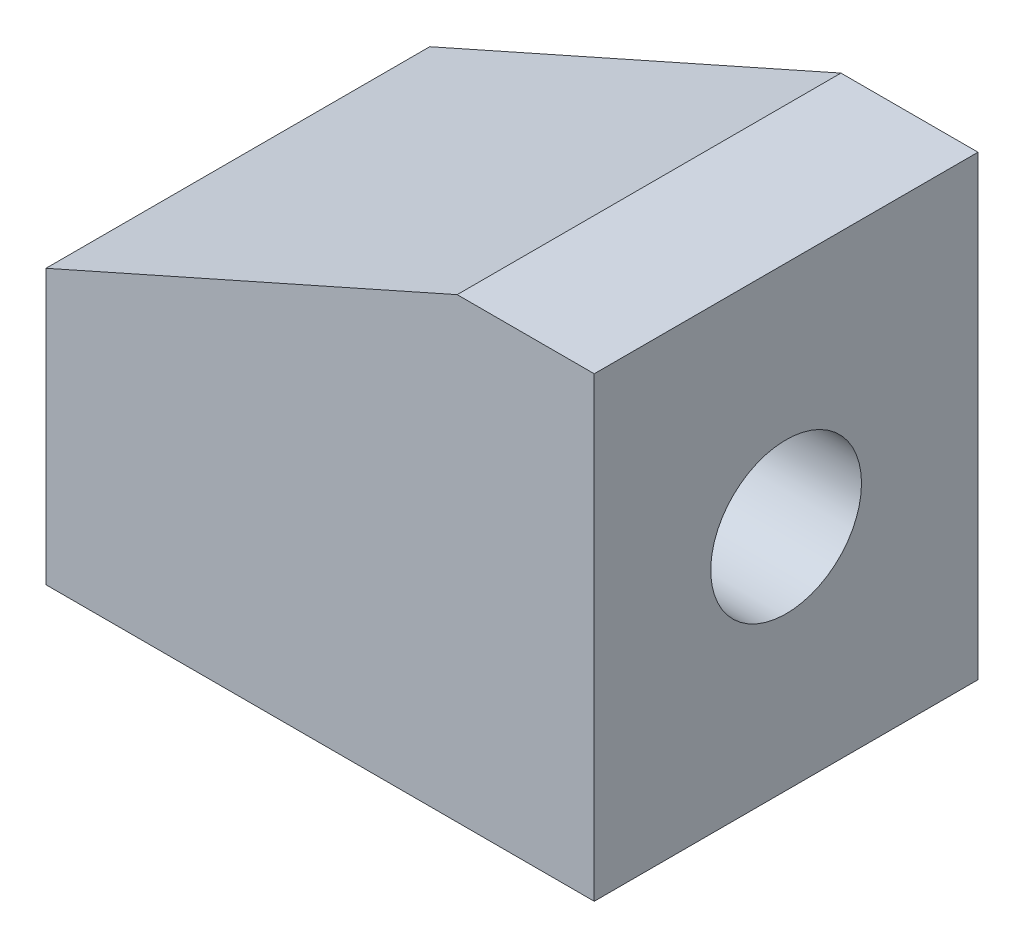
SolidWorks part; units mm, degrees
ref_plane "Front Plane" through (0, 0, 0) normal (0, 0, 1) x (1, 0, 0)
ref_plane "Top Plane" through (0, 0, 0) normal (0, 1, 0) x (1, 0, 0)
ref_plane "Right Plane" through (0, 0, 0) normal (1, 0, 0) x (0, 0, -1)
sketch "Sketch1" plane through (0, 0, 0) normal (0, 0, 1) x (1, 0, 0)
  line L0 (-30, 15) -> (15, 35)
  line L1 (-30, -15) -> (30, -15)
  line L2 (-30, -15) -> (-30, 15)
  line L5 (30, 35) -> (30, -15)
  line L6 (-30, 15) -> (30, -15) construction
  line L7 (15, 35) -> (30, 35)
  point P0 (0, 0)
  point P1 (0, 0)
  dimension "D1" = 60
  dimension "D2" = 30
  dimension "D3" = 15
  dimension "D4" = 50
  dimension "D5" = 35
extrude "Boss-Extrude1" add sketch "Sketch1" along normal blind 42
sketch "Sketch2" plane through (30, 0, 0) normal (1, 0, 0) x (0, 0, -1)
  line L0 (-42, -15) -> (0, -15) construction
  line L1 (-42, -15) -> (0, -15)
  line L2 (-21, -15) -> (-21, 10)
  point P5 (-21, 10)
  dimension "D1" = 25
hole_wizard "M18x1.5 Tapped Hole1" positions "3DSketch1" profile "Sketch4" tap size "M18x1.5" standard "ISO"
sketch3d "3DSketch1"
  point P0 (30, 10, 21)
sketch "Sketch4" plane through (30, 10, 21) normal (0, 1, 0) x (0, 0, -1)
  line L0 (0, 0) -> (0, 48.4571)
  line L1 (0, 48.4571) -> (8.25, 43.5)
  line L2 (8.25, 43.5) -> (8.25, 0)
  line L5 (8.25, 0) -> (0, 0)
  line L10 (0, 48.4571) -> (-8.25, 43.5) construction
  line L11 (0, -6.35) -> (0, 107.95) construction
  dimension "Tap Drill Dia." = 16.5
  dimension "Tap Drill Depth" = 43.5
  dimension "Drill Angle" = 118
cosmetic thread "Hole Thread1"
